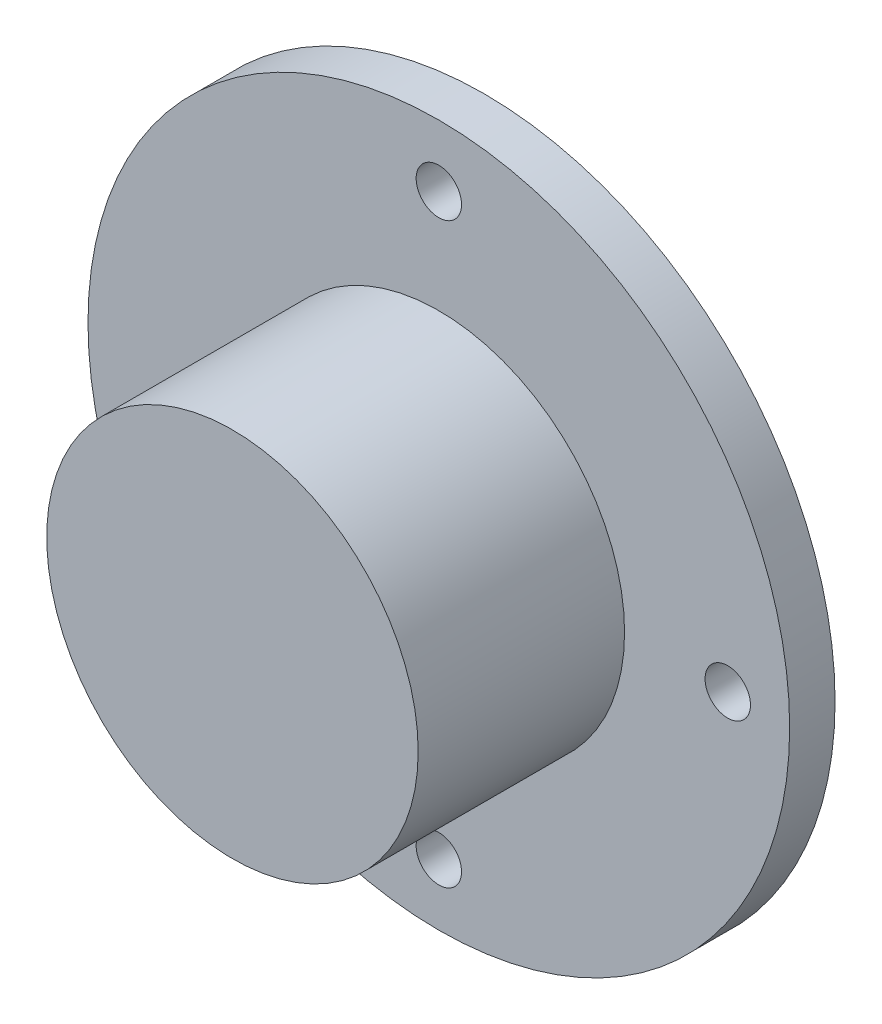
SolidWorks part; units mm, degrees
ref_plane "Front Plane" through (0, 0, 0) normal (0, 0, 1) x (1, 0, 0)
ref_plane "Top Plane" through (0, 0, 0) normal (0, 1, 0) x (1, 0, 0)
ref_plane "Right Plane" through (0, 0, 0) normal (1, 0, 0) x (0, 0, -1)
sketch "Outer_race_keeper_flange_profile" plane through (0, 0, 0) normal (0, 0, 1) x (1, 0, 0)
  circle A0 centre (0, 0) radius 17
  dimension "D1" = 34
extrude "Outer_race_keeper_flange" add sketch "Outer_race_keeper_flange_profile" along normal blind 2
sketch "Housing_contact_rim_preserves_bearing_float_profile" plane through (0, 0, 0) normal (0, 0, 1) x (1, 0, 0)
  circle A0 centre (0, 0) radius 17
  circle A1 centre (0, 0) radius 11.2
  dimension "D1" = 34
  dimension "D2" = 22.4
extrude "Housing_contact_rim_preserves_bearing_float" add sketch "Housing_contact_rim_preserves_bearing_float_profile" along normal blind 0.2 from offset 0.2
sketch "Pin_end_cover_profile" plane through (0, 0, 0) normal (0, 0, 1) x (1, 0, 0)
  circle A0 centre (0, 0) radius 9
  dimension "D1" = 18
extrude "Pin_end_cover" add sketch "Pin_end_cover_profile" along normal blind 12
sketch "Dowel_end_float_pocket_profile" plane through (0, 0, 0) normal (0, 0, 1) x (1, 0, 0)
  circle A0 centre (0, 0) radius 7
  dimension "D1" = 14
extrude "Dowel_end_float_pocket_depth9" cut sketch "Dowel_end_float_pocket_profile" along normal blind 9
sketch "Keeper_M2_fasteners_profile" plane through (0, 0, 0) normal (0, 0, 1) x (1, 0, 0)
  circle A0 centre (14, 0) radius 1.1
  circle A1 centre (0, -14) radius 1.1
  circle A2 centre (0, 14) radius 1.1
  dimension "D1" = 2.2
  dimension "D2" = 2.2
  dimension "D3" = 2.2
  dimension "D4" = 14
  dimension "D5" = 14
  dimension "D6" = 14
extrude "Keeper_M2_fasteners" cut sketch "Keeper_M2_fasteners_profile" along normal through all from offset 50
